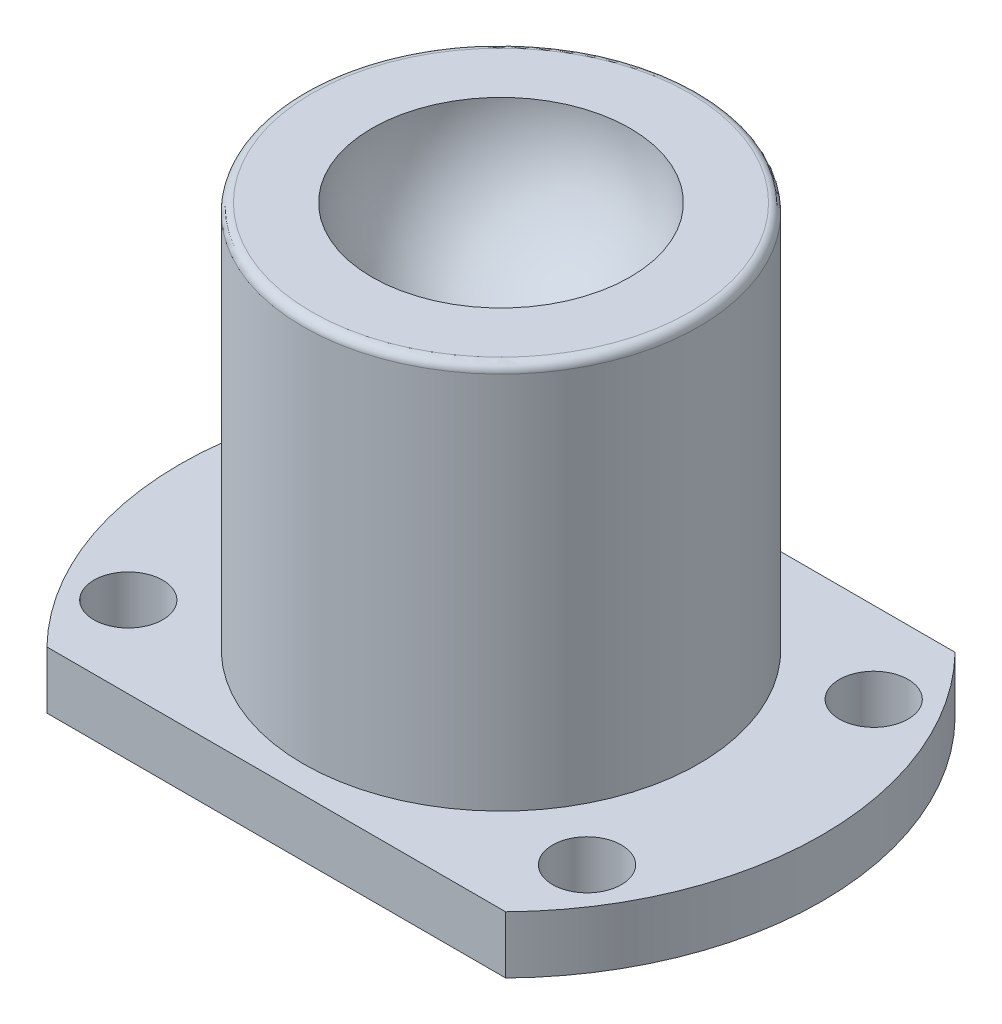
SolidWorks part; units mm, degrees
ref_plane "前视基准面" through (0, 0, 0) normal (0, 0, 1) x (1, 0, 0)
ref_plane "上视基准面" through (0, 0, 0) normal (0, 1, 0) x (1, 0, 0)
ref_plane "右视基准面" through (0, 0, 0) normal (1, 0, 0) x (0, 0, -1)
other "Configuration Table"
sketch "草图1" plane through (0, 0, 0) normal (0, 1, 0) x (1, 0, 0)
  circle A0 centre (0, 0) radius 11.2
  dimension "D1" = 22.4
extrude "凸台-拉伸1" add sketch "草图1" along normal blind 2
sketch "草图2" plane through (0, 2, 0) normal (0, 1, 0) x (1, 0, 0)
  line L1 (-8, -7.8384) -> (8, -7.8384)
  line L3 (-8, 7.8384) -> (8, 7.8384)
  circle A0 centre (0, 0) radius 11.2 construction
  arc A1 (8, -7.8384) -> (8, 7.8384) centre (0, 0) ccw
  circle A2 centre (0, 0) radius 11.2
  arc A3 (-8, 7.8384) -> (-8, -7.8384) centre (0, 0) ccw
  point P0 (0, 0)
  dimension "D2" = 16
  dimension "D3" = 16
  dimension "D1" = 0
extrude "切除-拉伸1" cut sketch "草图2" against normal blind 2 flip side to cut
sketch "草图3" plane through (0, 2, 0) normal (0, 1, 0) x (1, 0, 0)
  circle A0 centre (0, 0) radius 6.9
  dimension "D1" = 13.8
extrude "凸台-拉伸2" add sketch "草图3" along normal blind 13.5
sketch "草图4" plane through (0, 2, 0) normal (0, 1, 0) x (1, 0, 0)
  line L1 (-8, -5) -> (8, -5) construction
  line L2 (-8, -5) -> (-8, 5) construction
  line L3 (-8, 5) -> (8, 5) construction
  line L4 (8, -5) -> (8, 5) construction
  line L5 (-8, -5) -> (8, 5) construction
  line L6 (-8, 5) -> (8, -5) construction
  circle A0 centre (-8, 5) radius 1.2
  circle A1 centre (-8, -5) radius 1.2
  circle A2 centre (8, -5) radius 1.2
  circle A3 centre (8, 5) radius 1.2
  point P0 (0, 0)
  dimension "D3" = 2.4
  dimension "D4" = 2.4
  dimension "D5" = 2.4
  dimension "D6" = 2.4
  dimension "D1" = 16
  dimension "D2" = 10
extrude "切除-拉伸2" cut sketch "草图4" against normal blind 13.5
fillet "圆角1" radius 0.3 1 edges at (0, 15.5, 6.9)
sketch "草图5" plane through (0, 15.5, 0) normal (0, 1, 0) x (1, 0, 0)
  line L0 (0, -4.5) -> (0, 4.5) construction
  line L1 (0, 4.5) -> (0, -4.5)
  arc A0 (0, -4.5) -> (0, 4.5) centre (0, 0) ccw
  point P3 (0, 4.5)
  point P6 (0, 0)
  dimension "D1" = 9
revolve "切除-旋转1" cut sketch "草图5" angle 360 about L0
